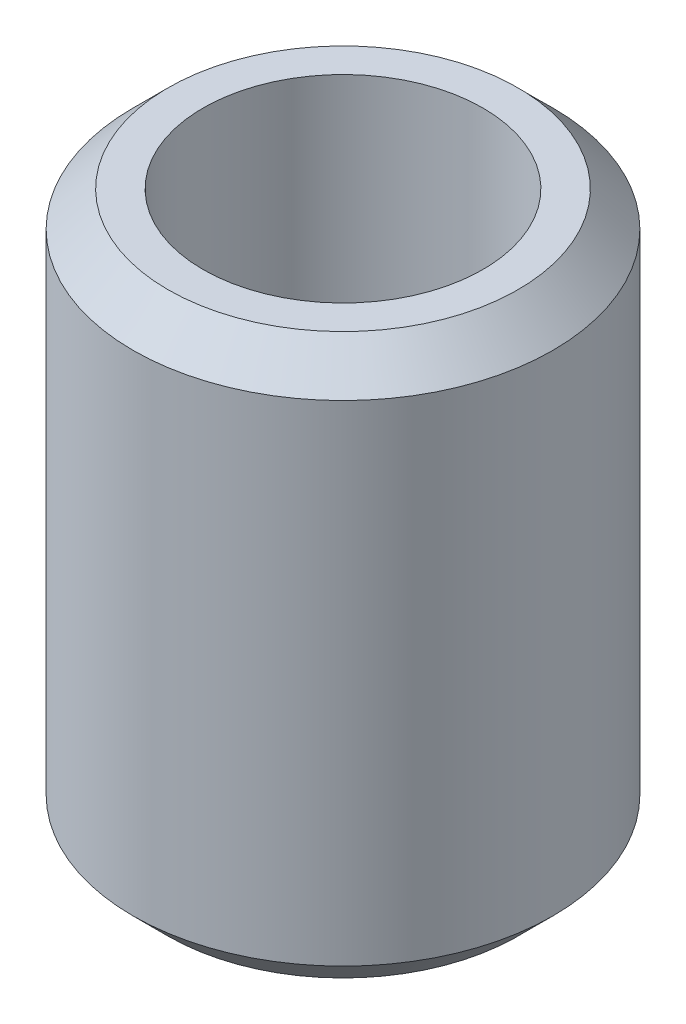
SolidWorks part; units mm, degrees
ref_plane "Front Plane" through (0, 0, 0) normal (0, 0, 1) x (1, 0, 0)
ref_plane "Top Plane" through (0, 0, 0) normal (0, 1, 0) x (1, 0, 0)
ref_plane "Right Plane" through (0, 0, 0) normal (1, 0, 0) x (0, 0, -1)
sketch "Sketch1" plane through (0, 0, 0) normal (1, 0, 0) x (0, 0, -1)
  line L0 (0, 7.0788) -> (0, -3.0061) construction
  line L1 (-2, 4) -> (-2.5, 4)
  line L2 (-2, -4) -> (-2.5, -4)
  line L3 (-3, -3.5) -> (-3, 3.5)
  line L4 (-2.5, 4) -> (-3, 3.5)
  line L5 (-2.5, -4) -> (-3, -3.5)
  line L6 (-2, 4) -> (-2, -4)
  line L7 (0, 4) -> (-2, 4) construction
  line L8 (0, -4) -> (-2, -4) construction
  point P4 (-3, 4)
  point P6 (-3, -4)
  point P13 (-3, 0)
  dimension "D1" = 8
  dimension "D2" = 6
  dimension "D3" = 4
revolve "Revolve1" add sketch "Sketch1" angle 360 about L0
